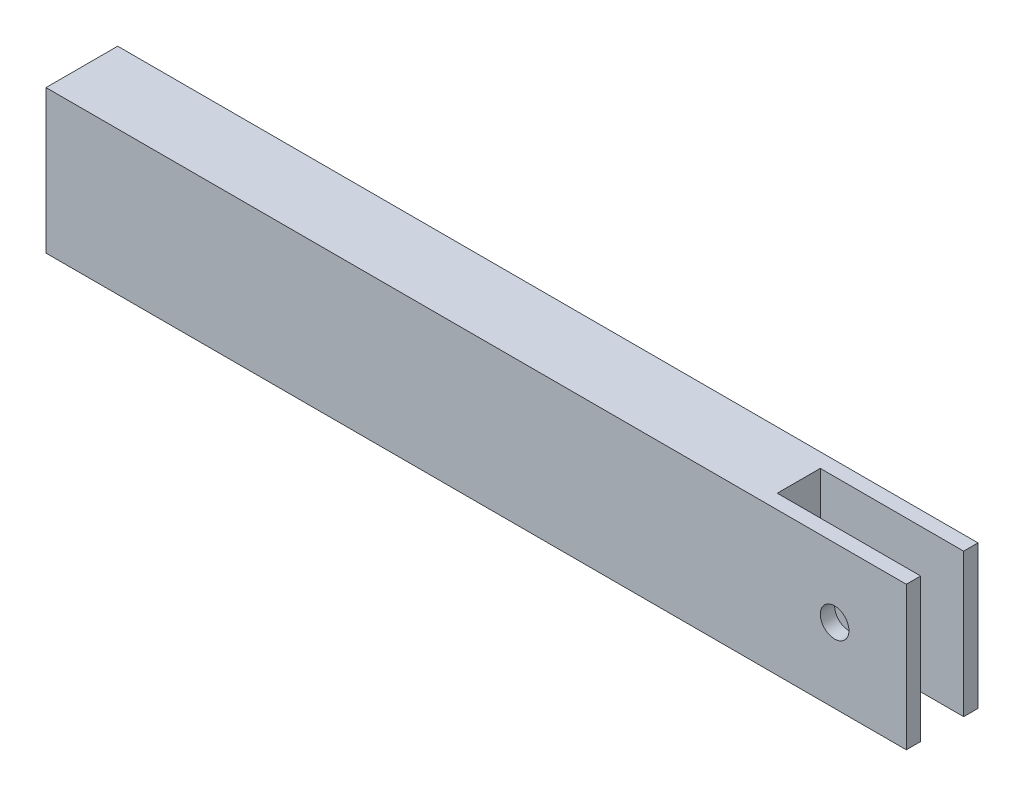
SolidWorks part; units mm, degrees
ref_plane "Front Plane" through (0, 0, 0) normal (0, 0, 1) x (1, 0, 0)
ref_plane "Top Plane" through (0, 0, 0) normal (0, 1, 0) x (1, 0, 0)
ref_plane "Right Plane" through (0, 0, 0) normal (1, 0, 0) x (0, 0, -1)
sketch "Sketch1" plane through (0, 0, 0) normal (0, 0, 1) x (1, 0, 0)
  line L1 (0, 0) -> (600, 0)
  line L2 (0, 0) -> (0, 100)
  line L3 (0, 100) -> (600, 100)
  line L4 (600, 0) -> (600, 100)
  dimension "D1" = 600
  dimension "D2" = 100
extrude "Boss-Extrude1" add sketch "Sketch1" along normal blind 50
sketch "Sketch2" plane through (600, 0, 0) normal (1, 0, 0) x (0, 0, -1)
  line L0 (-50, 100) -> (0, 100) construction
  line L1 (-40, 100) -> (-10, 100)
  line L2 (-40, 100) -> (-40, 0)
  line L3 (-40, 0) -> (-10, 0)
  line L4 (-10, 100) -> (-10, 0)
  line L5 (27.5, 0) -> (-27.5, 0) construction
  dimension "D1" = 30
  dimension "D2" = 10
extrude "Cut-Extrude1" cut sketch "Sketch2" against normal blind 100
sketch "Sketch3" plane through (0, 0, 10) normal (0, 0, 1) x (1, 0, 0)
  line L0 (600, 0) -> (600, 100) construction
  line L1 (600, 51.95) -> (0, 51.95) construction
  line L2 (0, -27.5) -> (0, 27.5) construction
  line L3 (550, 100) -> (550, 0) construction
  line L4 (500, 100) -> (600, 100) construction
  circle A0 centre (550, 51.95) radius 10
  point P12 (550, 51.95)
  dimension "D1" = 20
extrude "Cut-Extrude3" cut sketch "Sketch3" against normal through all both and the other way through all contours A0
